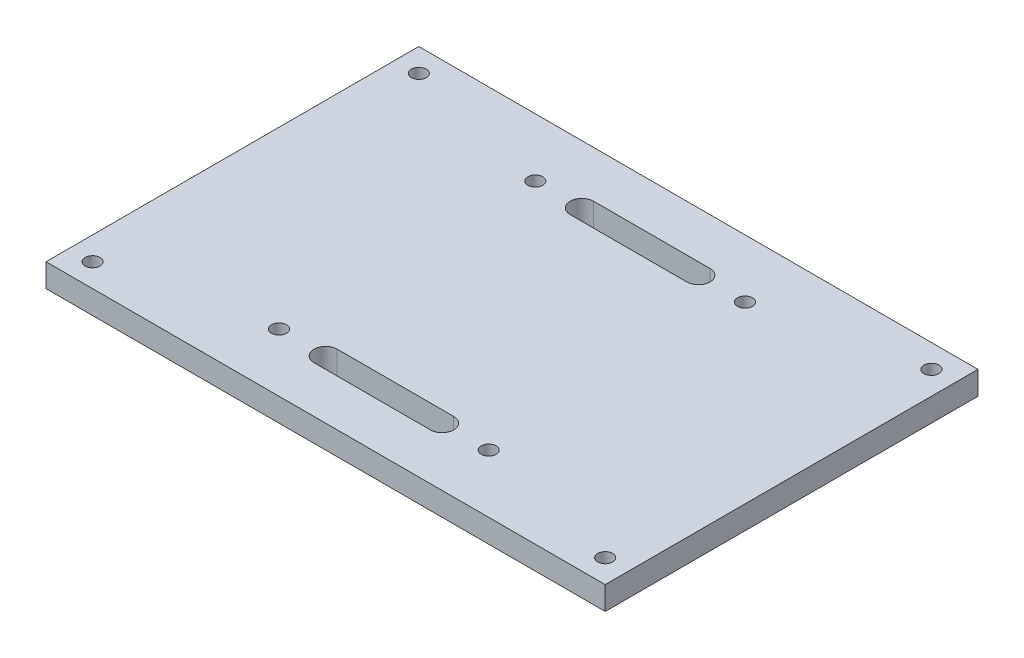
SolidWorks part; units mm, degrees
ref_plane "Plan de face" through (0, 0, 0) normal (0, 0, 1) x (1, 0, 0)
ref_plane "Plan de dessus" through (0, 0, 0) normal (0, 1, 0) x (1, 0, 0)
ref_plane "Plan de droite" through (0, 0, 0) normal (1, 0, 0) x (0, 0, -1)
sketch "Esquisse1" plane through (0, 0, 0) normal (0, 1, 0) x (1, 0, 0)
  line L1 (0, 0) -> (120, 0)
  line L2 (0, 0) -> (0, 80)
  line L3 (0, 80) -> (120, 80)
  line L4 (120, 0) -> (120, 80)
  dimension "D1" = 120
  dimension "D2" = 80
extrude "Boss.-Extru.1" add sketch "Esquisse1" along normal blind 5
sketch "Esquisse2" plane through (0, 5, 0) normal (0, 1, 0) x (1, 0, 0)
  line L0 (0, 67.5) -> (120, 67.5) construction
  line L1 (0, 80) -> (0, 0) construction
  line L2 (120, 0) -> (120, 80) construction
  line L3 (0, 40) -> (120, 40) construction
  line L4 (120, 80) -> (0, 80) construction
  line L5 (47.5, 67.5) -> (72.5, 67.5) construction
  line L6 (47.5, 70) -> (72.5, 70)
  line L7 (47.5, 65) -> (72.5, 65)
  line L8 (60, 80) -> (60, 0) construction
  line L9 (0, 0) -> (120, 0) construction
  line L10 (47.5, 12.5) -> (72.5, 12.5) construction
  line L11 (47.5, 10) -> (72.5, 10)
  line L12 (47.5, 15) -> (72.5, 15)
  circle A0 centre (37.5, 67.5) radius 1.6
  arc A2 (47.5, 70) -> (47.5, 65) centre (47.5, 67.5) ccw
  arc A3 (72.5, 65) -> (72.5, 70) centre (72.5, 67.5) ccw
  circle A4 centre (82.5, 67.5) radius 1.6
  circle A5 centre (82.5, 12.5) radius 1.6
  circle A6 centre (37.5, 12.5) radius 1.6
  arc A7 (47.5, 10) -> (47.5, 15) centre (47.5, 12.5) cw
  arc A8 (72.5, 15) -> (72.5, 10) centre (72.5, 12.5) cw
  circle A9 centre (5, 75) radius 1.6
  circle A10 centre (115, 75) radius 1.6
  circle A11 centre (115, 5) radius 1.6
  circle A12 centre (5, 5) radius 1.6
  point P14 (60, 67.5)
  point P31 (60, 12.5)
  point P38 (0, 0)
  point P39 (0, 0)
  point P42 (4.4019, 77.8968)
  dimension "D3" = 25
  dimension "D5" = 3.2
  dimension "D1" = 3.2
  dimension "D2" = 12.5
  dimension "D4" = 5
  dimension "D6" = 22.5
  dimension "D7" = 5
  dimension "D8" = 5
extrude "Enlèv. mat.-Extru.1" cut sketch "Esquisse2" against normal through all
